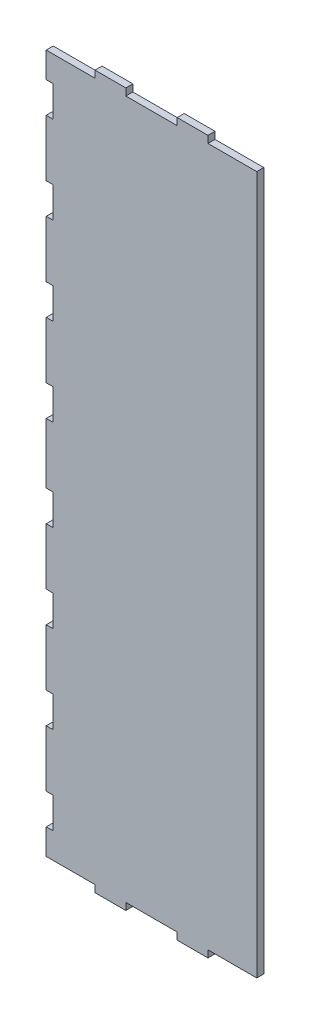
SolidWorks part; units mm, degrees
ref_plane "Front Plane" through (0, 0, 0) normal (0, 0, 1) x (1, 0, 0)
ref_plane "Top Plane" through (0, 0, 0) normal (0, 1, 0) x (1, 0, 0)
ref_plane "Right Plane" through (0, 0, 0) normal (1, 0, 0) x (0, 0, -1)
sketch "Sketch1" plane through (0, 0, 0) normal (0, 0, 1) x (1, 0, 0)
  line L1 (-65.0875, -215.9) -> (65.0875, -215.9)
  line L2 (-65.0875, -215.9) -> (-65.0875, 215.9)
  line L3 (-65.0875, 215.9) -> (65.0875, 215.9)
  line L4 (65.0875, -215.9) -> (65.0875, 215.9)
  line L5 (-65.0875, -215.9) -> (65.0875, 215.9) construction
  line L6 (-65.0875, 215.9) -> (65.0875, -215.9) construction
  point P0 (0, 0)
  dimension "D1" = 130.175
  dimension "D2" = 431.8
extrude "Boss-Extrude1" add sketch "Sketch1" along normal blind 4.3434
sketch "Sketch2" plane through (0, 0, 4.3434) normal (0, 0, 1) x (1, 0, 0)
  line L0 (-65.0875, 215.9) -> (-65.0875, -215.9) construction
  line L1 (-69.4309, 180.975) -> (-60.7441, 180.975)
  line L2 (-69.4309, 180.975) -> (-69.4309, 200.025)
  line L3 (-69.4309, 200.025) -> (-60.7441, 200.025)
  line L4 (-60.7441, 180.975) -> (-60.7441, 200.025)
  line L5 (-69.4309, 180.975) -> (-60.7441, 200.025) construction
  line L6 (-69.4309, 200.025) -> (-60.7441, 180.975) construction
  line L7 (65.0875, 215.9) -> (-65.0875, 215.9) construction
  line L8 (-34.925, 211.5566) -> (-15.875, 211.5566)
  line L9 (-34.925, 211.5566) -> (-34.925, 220.2434)
  line L10 (-34.925, 220.2434) -> (-15.875, 220.2434)
  line L11 (-15.875, 211.5566) -> (-15.875, 220.2434)
  line L12 (-34.925, 211.5566) -> (-15.875, 220.2434) construction
  line L13 (-34.925, 220.2434) -> (-15.875, 211.5566) construction
  line L14 (15.875, 220.2434) -> (34.925, 220.2434)
  line L15 (34.925, 211.5566) -> (34.925, 220.2434)
  line L16 (15.875, 211.5566) -> (34.925, 211.5566)
  line L17 (15.875, 211.5566) -> (15.875, 220.2434)
  line L31 (-69.4309, 145.923) -> (-60.7441, 145.923)
  line L32 (-60.7441, 126.873) -> (-60.7441, 145.923)
  line L33 (-69.4309, 126.873) -> (-60.7441, 126.873)
  line L34 (-69.4309, 126.873) -> (-69.4309, 145.923)
  line L35 (-69.4309, 91.821) -> (-60.7441, 91.821)
  line L36 (-60.7441, 72.771) -> (-60.7441, 91.821)
  line L37 (-69.4309, 72.771) -> (-60.7441, 72.771)
  line L38 (-69.4309, 72.771) -> (-69.4309, 91.821)
  line L39 (-69.4309, 37.719) -> (-60.7441, 37.719)
  line L40 (-60.7441, 18.669) -> (-60.7441, 37.719)
  line L41 (-69.4309, 18.669) -> (-60.7441, 18.669)
  line L42 (-69.4309, 18.669) -> (-69.4309, 37.719)
  line L60 (-69.4309, -16.383) -> (-60.7441, -16.383) [skipped]
  line L61 (-60.7441, -35.433) -> (-60.7441, -16.383) [skipped]
  line L62 (-69.4309, -35.433) -> (-60.7441, -35.433) [skipped]
  line L63 (-69.4309, -35.433) -> (-69.4309, -16.383) [skipped]
  line L64 (-69.4309, -70.485) -> (-60.7441, -70.485) [skipped]
  line L65 (-60.7441, -89.535) -> (-60.7441, -70.485) [skipped]
  line L66 (-69.4309, -89.535) -> (-60.7441, -89.535) [skipped]
  line L67 (-69.4309, -89.535) -> (-69.4309, -70.485) [skipped]
  line L68 (-69.4309, -124.587) -> (-60.7441, -124.587) [skipped]
  line L69 (-60.7441, -143.637) -> (-60.7441, -124.587) [skipped]
  line L70 (-69.4309, -143.637) -> (-60.7441, -143.637) [skipped]
  line L71 (-69.4309, -143.637) -> (-69.4309, -124.587) [skipped]
  line L72 (-69.4309, -178.689) -> (-60.7441, -178.689) [skipped]
  line L73 (-60.7441, -197.739) -> (-60.7441, -178.689) [skipped]
  line L74 (-69.4309, -197.739) -> (-60.7441, -197.739) [skipped]
  line L75 (-69.4309, -197.739) -> (-69.4309, -178.689) [skipped]
  line L76 (66.675, 220.2434) -> (85.725, 220.2434) [skipped]
  line L77 (85.725, 211.5566) -> (85.725, 220.2434) [skipped]
  line L78 (66.675, 211.5566) -> (85.725, 211.5566) [skipped]
  line L79 (66.675, 211.5566) -> (66.675, 220.2434) [skipped]
  line L80 (117.475, 220.2434) -> (136.525, 220.2434) [skipped]
  line L81 (136.525, 211.5566) -> (136.525, 220.2434) [skipped]
  line L82 (117.475, 211.5566) -> (136.525, 211.5566) [skipped]
  line L83 (117.475, 211.5566) -> (117.475, 220.2434) [skipped]
  line L84 (168.275, 220.2434) -> (187.325, 220.2434) [skipped]
  line L85 (187.325, 211.5566) -> (187.325, 220.2434) [skipped]
  line L86 (168.275, 211.5566) -> (187.325, 211.5566) [skipped]
  line L87 (168.275, 211.5566) -> (168.275, 220.2434) [skipped]
  point P0 (-65.0875, 190.5)
  point P7 (-25.4, 215.9)
  dimension "D1" = 8.6868
  dimension "D2" = 8.6868
  dimension "D3" = 19.05
  dimension "D4" = 19.05
  dimension "D5" = 39.6875
  dimension "D6" = 25.4
  dimension "D7" = 5
  dimension "D8" = 8
extrude "Cut-Extrude1" cut sketch "Sketch2" against normal through all
mirror "Mirror1" about plane through (0, 0, 0) normal (0, 1, 0) of "Cut-Extrude1"
sketch "Sketch3" plane through (0, 0, 0) normal (0, 0, 1) x (1, 0, 0)
  line L8 (-34.925, 211.5566) -> (-15.875, 211.5566)
  line L9 (-34.925, 211.5566) -> (-34.925, 220.2434)
  line L10 (-34.925, 220.2434) -> (-15.875, 220.2434)
  line L11 (-15.875, 211.5566) -> (-15.875, 220.2434)
  line L12 (-34.925, 211.5566) -> (-15.875, 220.2434) construction
  line L13 (-34.925, 220.2434) -> (-15.875, 211.5566) construction
  line L14 (15.875, 220.2434) -> (34.925, 220.2434)
  line L15 (34.925, 211.5566) -> (34.925, 220.2434)
  line L16 (15.875, 211.5566) -> (34.925, 211.5566)
  line L17 (15.875, 211.5566) -> (15.875, 220.2434)
  line L76 (66.675, 220.2434) -> (85.725, 220.2434) [skipped]
  line L77 (85.725, 211.5566) -> (85.725, 220.2434) [skipped]
  line L78 (66.675, 211.5566) -> (85.725, 211.5566) [skipped]
  line L79 (66.675, 211.5566) -> (66.675, 220.2434) [skipped]
  line L80 (117.475, 220.2434) -> (136.525, 220.2434) [skipped]
  line L81 (136.525, 211.5566) -> (136.525, 220.2434) [skipped]
  line L82 (117.475, 211.5566) -> (136.525, 211.5566) [skipped]
  line L83 (117.475, 211.5566) -> (117.475, 220.2434) [skipped]
  line L84 (168.275, 220.2434) -> (187.325, 220.2434) [skipped]
  line L85 (187.325, 211.5566) -> (187.325, 220.2434) [skipped]
  line L86 (168.275, 211.5566) -> (187.325, 211.5566) [skipped]
  line L87 (168.275, 211.5566) -> (168.275, 220.2434) [skipped]
  point P7 (-25.4, 215.9)
  dimension "D2" = 8.6868
  dimension "D3" = 19.05
  dimension "D7" = 5
extrude "Boss-Extrude2" add sketch "Sketch3" along normal up to surface (4.3434 mm away) up to face at (-38.7174, 0, 4.3434)
mirror "Mirror2" about plane through (0, 0, 0) normal (0, 1, 0) of "Boss-Extrude2"
